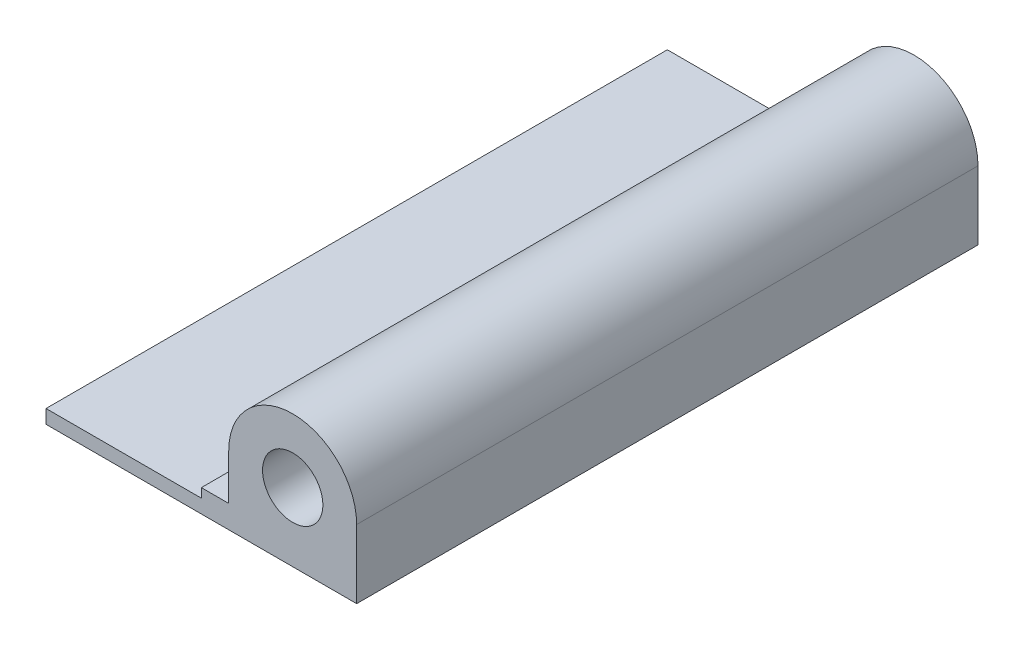
SolidWorks part; units mm, degrees
material "CA"
ref_plane "Спереди" through (0, 0, 0) normal (0, 0, 1) x (1, 0, 0)
ref_plane "Сверху" through (0, 0, 0) normal (0, 1, 0) x (1, 0, 0)
ref_plane "Справа" through (0, 0, 0) normal (1, 0, 0) x (0, 0, -1)
ref_plane "Плоскость4" through (0, 0, 68) normal (0, 0, 1) x (1, 0, 0)
sketch "Эскиз1" plane through (0, 0, 68) normal (0, 0, 1) x (1, 0, 0)
  line L0 (20, 7.5) -> (20, 2.5)
  line L1 (20, 2.5) -> (17, 2.5)
  line L2 (17, 2.5) -> (17, 1.5)
  line L3 (17, 1.5) -> (0, 1.5)
  line L4 (0, 1.5) -> (0, 0)
  line L5 (0, 0) -> (34, 0)
  line L6 (34, 0) -> (34, 7.5)
  circle A0 centre (27, 7.5) radius 3.3
  arc A1 (34, 7.5) -> (20, 7.5) centre (27, 7.5) ccw
extrude "Бобышка-Вытянуть1" add sketch "Эскиз1" against normal blind 68
